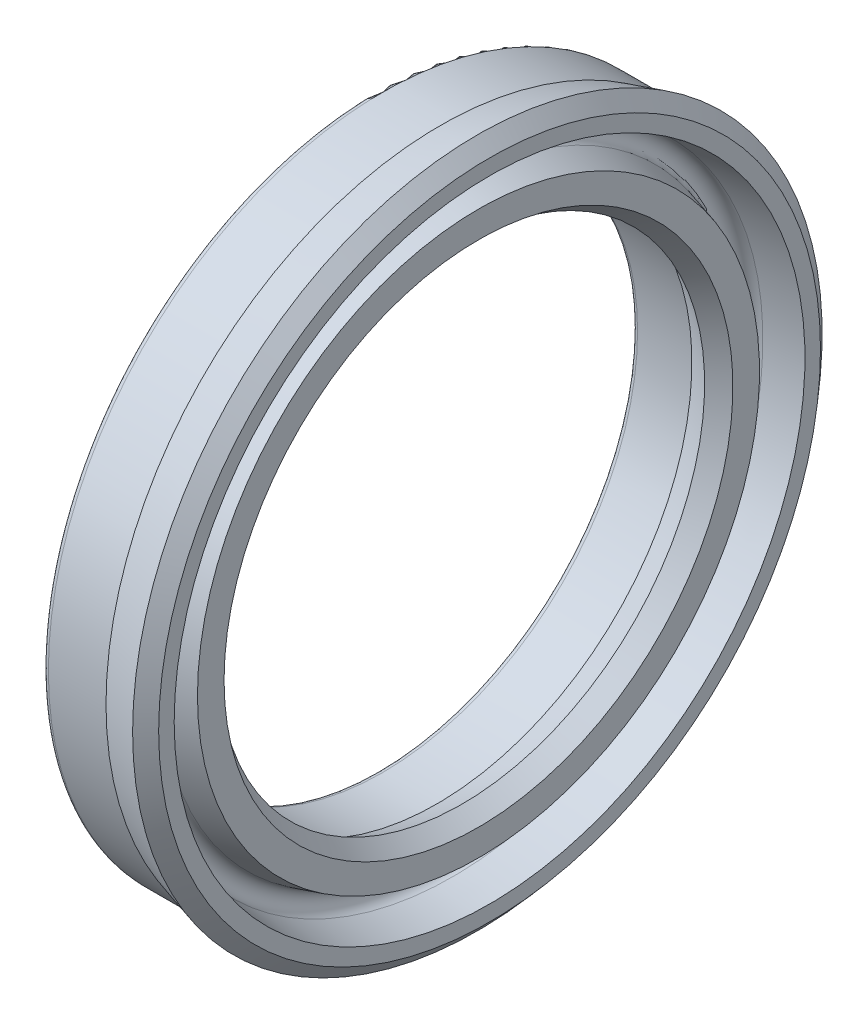
SolidWorks part; units mm, degrees
material "Trygonal HPU dietweiss"
ref_plane "Front Plane" through (0, 0, 0) normal (0, 0, 1) x (1, 0, 0)
ref_plane "Top Plane" through (0, 0, 0) normal (0, 1, 0) x (1, 0, 0)
ref_plane "Right Plane" through (0, 0, 0) normal (1, 0, 0) x (0, 0, -1)
sketch "Sketch1" plane through (0, 0, 0) normal (0, 0, 1) x (1, 0, 0)
  line L0 (0, 0) -> (70.2538, 0) construction
  line L1 (0, 23) -> (0, 30.15)
  line L2 (0, 30.15) -> (5.7, 30.15)
  line L3 (9.15, 22.95) -> (7.65, 21.9)
  line L4 (10.15, 29.85) -> (10.15, 28.45)
  line L5 (10.15, 28.45) -> (6.8136, 27.9907)
  line L6 (9.15, 25.35) -> (9.15, 22.95)
  line L7 (6.682, 26.0366) -> (9.15, 25.35)
  line L9 (0, 23) -> (5.4, 23)
  line L10 (5.4, 23) -> (7.65, 21.9)
  line L11 (5.7, 30.15) -> (9.05, 31.1)
  line L12 (9.05, 31.1) -> (10.15, 29.85)
  arc A0 (6.682, 26.0366) -> (6.8136, 27.9907) centre (6.95, 27) cw
  dimension "D13" = 1
  dimension "D15" = 1.5
  dimension "D16" = 54
  dimension "D17" = 4.2
  dimension "D1" = 46
  dimension "D2" = 43.8
  dimension "D3" = 10.15
  dimension "D4" = 5.4
  dimension "D5" = 60.3
  dimension "D6" = 1
  dimension "D7" = 59.7
  dimension "D8" = 45.9
  dimension "D9" = 5.7
  dimension "D10" = 62.2
  dimension "D11" = 1.1
  dimension "D12" = 1.4
  dimension "D14" = 2.4
revolve "Revolve1" add sketch "Sketch1" angle 360 about L0
fillet "Fillet1" radius 0.5 2 edges at (0, 0, 23) (0, 0, 30.15)
